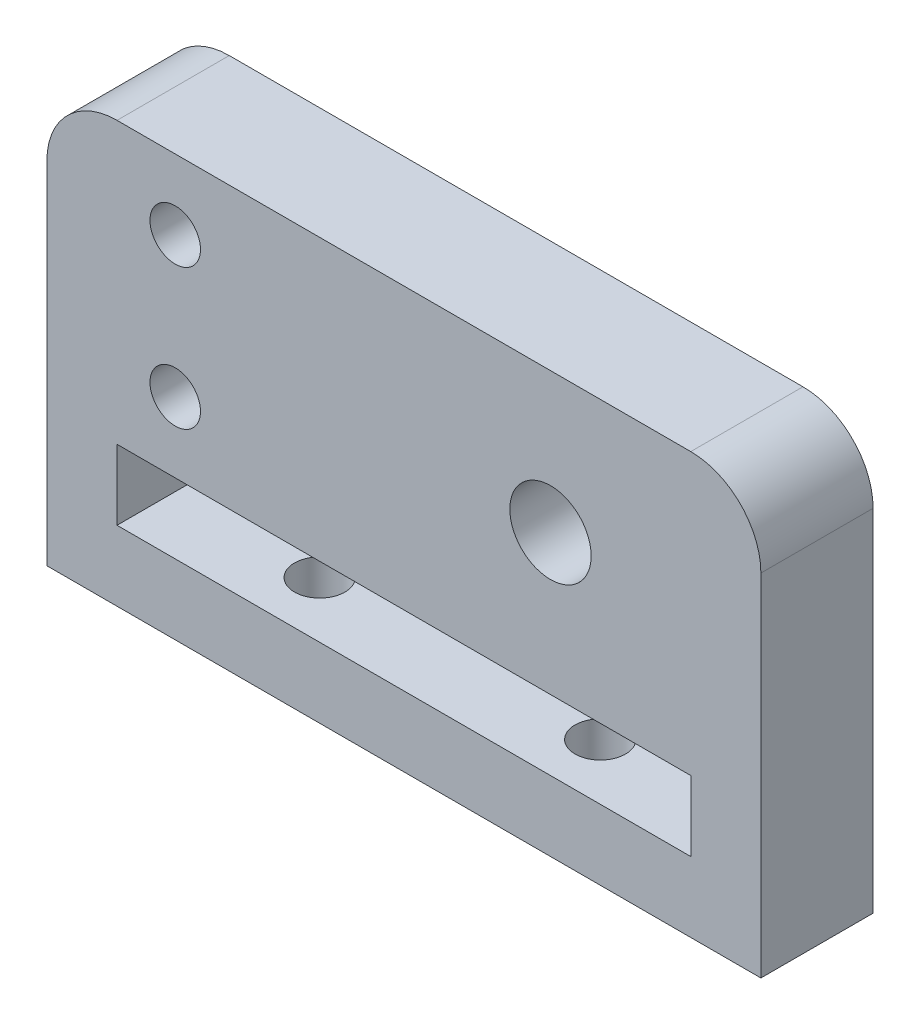
SolidWorks part; units mm, degrees
ref_plane "Plan de face" through (0, 0, 0) normal (0, 0, 1) x (1, 0, 0)
ref_plane "Plan de dessus" through (0, 0, 0) normal (0, 1, 0) x (1, 0, 0)
ref_plane "Plan de droite" through (0, 0, 0) normal (1, 0, 0) x (0, 0, -1)
sketch "Esquisse1" plane through (0, 0, 0) normal (0, 0, 1) x (1, 0, 0)
  line L0 (0, 0) -> (0, 30)
  line L1 (0, 0) -> (50.9, 0)
  line L2 (0, 30) -> (50.9, 30)
  line L3 (50.9, 0) -> (50.9, 30)
  line L4 (5, 10) -> (5, 5)
  line L5 (5, 10) -> (45.9, 10)
  line L6 (5, 5) -> (45.9, 5)
  line L7 (45.9, 10) -> (45.9, 5)
  circle A0 centre (35.9, 20) radius 2.9
  dimension "D9" = 5.8
  dimension "D1" = 50.9
  dimension "D2" = 30
  dimension "D3" = 5
  dimension "D4" = 5
  dimension "D5" = 5
  dimension "D6" = 5
  dimension "D7" = 15
  dimension "D8" = 10
extrude "Boss.-Extru.1" add sketch "Esquisse1" along normal blind 8
sketch "Esquisse2" plane through (0, 0, 0) normal (0, -1, 0) x (1, 0, 0)
  line L0 (0, 8) -> (50.9, 8) construction
  line L1 (0, 0) -> (50.9, 0) construction
  circle A0 centre (15.45, 4) radius 1.8
  circle A1 centre (35.45, 4) radius 1.8
  point P6 (25.45, 8)
  dimension "D1" = 3.6
  dimension "D2" = 3.6
  dimension "D3" = 20
  dimension "D4" = 10
  dimension "D5" = 4
  dimension "D6" = 4
extrude "Enlèv. mat.-Extru.1" cut sketch "Esquisse2" against normal blind 15 contours A0 | A1
fillet "Congé1" radius 5 2 edges at (50.9, 30, 4) (0, 30, 4)
sketch "Esquisse3" plane through (0, 0, 0) normal (0, 0, -1) x (-1, 0, 0)
  line L0 (-45.9, 30) -> (-5, 30) construction
  line L1 (0, 25) -> (0, 0) construction
  circle A0 centre (-9.15, 25) radius 1.8
  circle A1 centre (-9.15, 15) radius 1.8
  dimension "D5" = 3.6
  dimension "D6" = 3.6
  dimension "D1" = 10
  dimension "D2" = 5
  dimension "D3" = 9.15
  dimension "D4" = 9.15
extrude "Enlèv. mat.-Extru.2" cut sketch "Esquisse3" against normal blind 10
sketch "Esquisse4" plane through (0, 10, 0) normal (0, -1, 0) x (1, 0, 0)
  circle A0 centre (15.45, 4) radius 3.5
  circle A1 centre (35.45, 4) radius 3.5
  dimension "D1" = 7
  dimension "D2" = 7
extrude "Enlèv. mat.-Extru.3" cut sketch "Esquisse4" against normal blind 3.5
